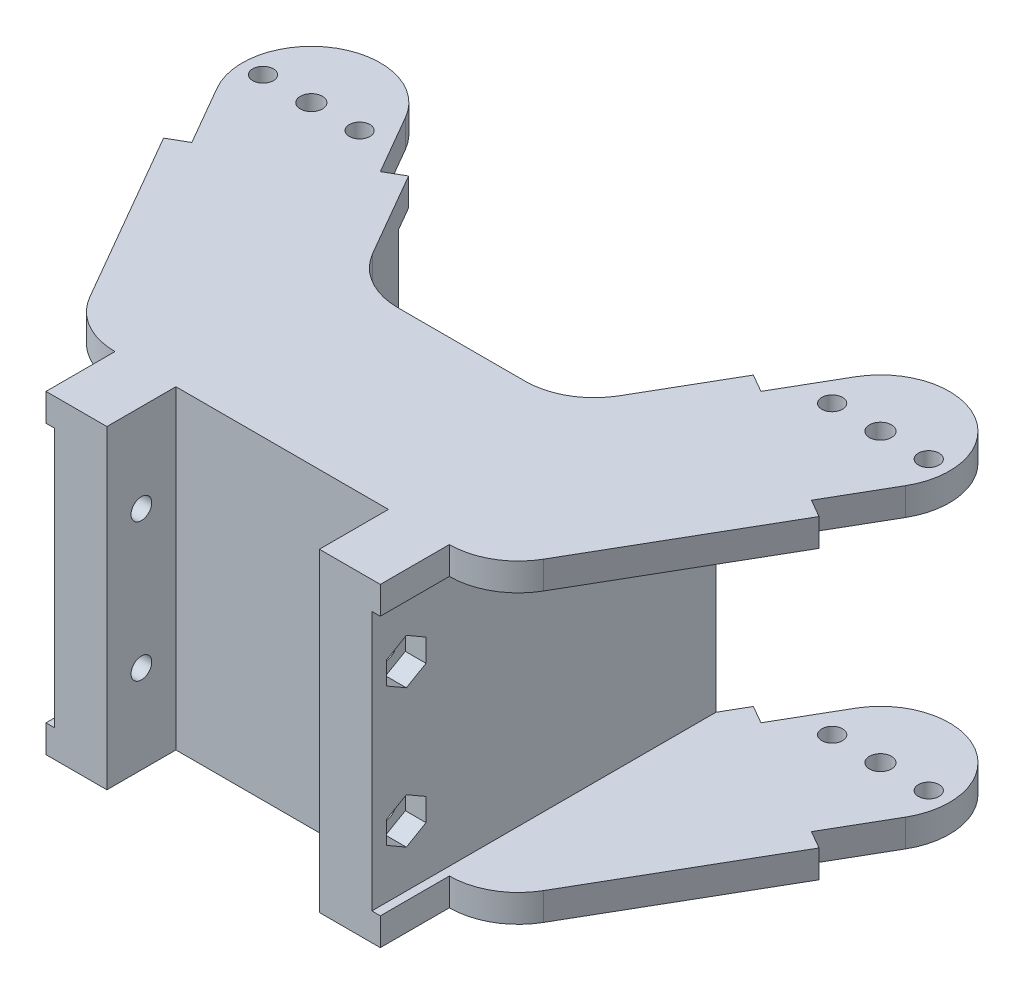
SolidWorks part; units mm, degrees
ref_plane "Alzado" through (0, 0, 0) normal (0, 0, 1) x (1, 0, 0)
ref_plane "Planta" through (0, 0, 0) normal (0, 1, 0) x (1, 0, 0)
ref_plane "Vista lateral" through (0, 0, 0) normal (1, 0, 0) x (0, 0, -1)
ref_plane "Plano1" through (0, -45.6, 0) normal (0, -1, 0) x (1, 0, 0)
sketch "Croquis1" plane through (0, -45.6, 0) normal (0, -1, 0) x (1, 0, 0)
  line L0 (65.4682, 45.4711) -> (17.0152, 45.4711)
  line L1 (8.3549, 40.4711) -> (-6.2583, 15.1603)
  line L2 (-6.2583, 15.1603) -> (-3.6603, 13.6603)
  line L3 (-3.6603, 13.6603) -> (-8.6603, 5)
  line L4 (8.6603, -5) -> (13.6603, 3.6603)
  line L5 (13.6603, 3.6603) -> (16.2583, 2.1603)
  line L6 (16.2583, 2.1603) -> (26.2528, 19.4711)
  line L7 (26.2528, 19.4711) -> (56.2306, 19.4711)
  line L8 (56.2306, 19.4711) -> (66.225, 2.1603)
  line L9 (66.225, 2.1603) -> (68.8231, 3.6603)
  line L10 (68.8231, 3.6603) -> (73.8231, -5)
  line L11 (91.1436, 5) -> (86.1436, 13.6603)
  line L12 (86.1436, 13.6603) -> (88.7417, 15.1603)
  line L13 (88.7417, 15.1603) -> (74.1284, 40.4711)
  arc A0 (74.1284, 40.4711) -> (65.4682, 45.4711) centre (65.4682, 35.4711) ccw
  arc A1 (17.0152, 45.4711) -> (8.3549, 40.4711) centre (17.0152, 35.4711) ccw
  arc A2 (-8.6603, 5) -> (8.6603, -5) centre (0, 0) ccw
  arc A3 (73.8231, -5) -> (91.1436, 5) centre (82.4833, 0) ccw
extrude "Saliente-Extruir1" add sketch "Croquis1" against normal blind 45.6
ref_plane "Plano2" through (0, -4, 0) normal (0, 1, 0) x (1, 0, 0)
sketch "Croquis2" plane through (0, -4, 0) normal (0, 1, 0) x (1, 0, 0)
  line L0 (64.2417, -45.4711) -> (65.4682, -45.4711)
  line L1 (74.1284, -40.4711) -> (88.7417, -15.1603)
  line L2 (88.7417, -15.1603) -> (86.1436, -13.6603)
  line L3 (86.1436, -13.6603) -> (91.1436, -5)
  line L4 (73.8231, 5) -> (68.8231, -3.6603)
  line L5 (68.8231, -3.6603) -> (66.225, -2.1603)
  line L6 (66.225, -2.1603) -> (64.2417, -5.5955)
  line L7 (64.2417, -5.5955) -> (64.2417, -45.4711)
  arc A0 (65.4682, -45.4711) -> (74.1284, -40.4711) centre (65.4682, -35.4711) ccw
  arc A1 (91.1436, -5) -> (73.8231, 5) centre (82.4833, 0) ccw
extrude "Cortar-Extruir1" cut sketch "Croquis2" against normal blind 37.6
ref_plane "Plano3" through (0, -41.6, 0) normal (0, -1, 0) x (1, 0, 0)
sketch "Croquis3" plane through (0, -41.6, 0) normal (0, -1, 0) x (1, 0, 0)
  line L0 (18.2417, 5.5955) -> (18.2417, 45.4711)
  line L1 (18.2417, 45.4711) -> (17.0152, 45.4711)
  line L2 (8.3549, 40.4711) -> (-6.2583, 15.1603)
  line L3 (-6.2583, 15.1603) -> (-3.6603, 13.6603)
  line L4 (-3.6603, 13.6603) -> (-8.6603, 5)
  line L5 (8.6603, -5) -> (13.6603, 3.6603)
  line L6 (13.6603, 3.6603) -> (16.2583, 2.1603)
  line L7 (16.2583, 2.1603) -> (18.2417, 5.5955)
  arc A0 (17.0152, 45.4711) -> (8.3549, 40.4711) centre (17.0152, 35.4711) ccw
  arc A1 (-8.6603, 5) -> (8.6603, -5) centre (0, 0) ccw
extrude "Cortar-Extruir2" cut sketch "Croquis3" against normal blind 37.6
sketch "Croquis4" plane through (0, 0, 45.4711) normal (0, 0, 1) x (1, 0, 0)
  line L0 (65.4682, -45.6) -> (17.0152, -45.6)
  line L1 (17.0152, -45.6) -> (17.0152, -41.6)
  line L2 (17.0152, -41.6) -> (18.2417, -41.6)
  line L3 (18.2417, -41.6) -> (18.2417, -4)
  line L4 (18.2417, -4) -> (17.0152, -4)
  line L5 (17.0152, -4) -> (17.0152, 0)
  line L6 (17.0152, 0) -> (65.4682, 0)
  line L7 (65.4682, 0) -> (65.4682, -4)
  line L8 (65.4682, -4) -> (64.2417, -4)
  line L9 (64.2417, -4) -> (64.2417, -41.6)
  line L10 (64.2417, -41.6) -> (65.4682, -41.6)
  line L11 (65.4682, -41.6) -> (65.4682, -45.6)
extrude "Saliente-Extruir2" add sketch "Croquis4" along normal blind 10
sketch "Croquis5" plane through (0, 0, 0) normal (0, 1, 0) x (-1, 0, 0)
  line L0 (-25.8417, 55.4711) -> (-56.6417, 55.4711)
  line L1 (-56.6417, 55.4711) -> (-56.6417, 45.4711)
  line L2 (-56.6417, 45.4711) -> (-25.8417, 45.4711)
  line L3 (-25.8417, 45.4711) -> (-25.8417, 55.4711)
extrude "Cortar-Extruir3" cut sketch "Croquis5" against normal through all
sketch "Croquis6" plane through (64.2417, 0, 0) normal (1, 0, 0) x (0, 0, -1)
  line L0 (-47.6207, -34.4446) -> (-47.6216, -31.1538)
  line L1 (-47.6216, -31.1538) -> (-50.4721, -29.5091)
  line L2 (-50.4721, -29.5091) -> (-53.3216, -31.1554)
  line L3 (-53.3216, -31.1554) -> (-53.3207, -34.4462)
  line L4 (-53.3207, -34.4462) -> (-50.4702, -36.0909)
  line L5 (-50.4702, -36.0909) -> (-47.6207, -34.4446)
extrude "Cortar-Extruir4" cut sketch "Croquis6" against normal blind 3
sketch "Croquis7" plane through (64.2417, 0, 0) normal (1, 0, 0) x (0, 0, -1)
  line L0 (-50.4702, -9.5091) -> (-53.3207, -11.1538)
  line L1 (-53.3207, -11.1538) -> (-53.3216, -14.4446)
  line L2 (-53.3216, -14.4446) -> (-50.4721, -16.0909)
  line L3 (-50.4721, -16.0909) -> (-47.6216, -14.4462)
  line L4 (-47.6216, -14.4462) -> (-47.6207, -11.1554)
  line L5 (-47.6207, -11.1554) -> (-50.4702, -9.5091)
extrude "Cortar-Extruir5" cut sketch "Croquis7" against normal blind 3
hole_wizard "Diámetro de taladro Ø3.0 (3)1" positions "Croquis9" profile "Croquis8" hole size "Ø3.0" standard "Ansi Metric"
sketch "Croquis9" plane through (25.8417, 0, 0) normal (1, 0, 0) x (0, 0, -1)
  point P0 (-50.4711, -12.8)
  point P1 (-50.4711, -32.8)
sketch "Croquis8" plane through (25.8417, -12.8, 50.4711) normal (0, 1, 0) x (0, 0, -1)
  line L0 (0, 0) -> (0, 35.8417)
  line L1 (0, 35.8417) -> (1.5, 35.8417)
  line L2 (1.5, 35.8417) -> (1.5, 0)
  line L5 (1.5, 0) -> (0, 0)
  line L11 (0, -6.35) -> (0, 107.95) construction
  dimension "Diámetro de taladro hasta el siguiente" = 3
  dimension "Profundidad de taladro hasta el siguiente" = 35.8417
hole_wizard "Diámetro de taladro Ø3.0 (3)2" positions "Croquis11" profile "Croquis10" hole size "Ø3.0" standard "Ansi Metric"
sketch "Croquis11" plane through (0, -45.6, 0) normal (0, -1, 0) x (-1, 0, 0)
  point P0 (-89.4833, 0)
  point P1 (-75.4833, 0)
sketch "Croquis10" plane through (89.4833, -45.6, 0) normal (1, 0, 0) x (0, 0, -1)
  line L0 (0, 0) -> (0, 4)
  line L1 (0, 4) -> (1.5, 4)
  line L2 (1.5, 4) -> (1.5, 0)
  line L5 (1.5, 0) -> (0, 0)
  line L11 (0, -6.35) -> (0, 107.95) construction
  dimension "Diámetro de taladro hasta el siguiente" = 3
  dimension "Profundidad de taladro hasta el siguiente" = 4
hole_wizard "Diámetro de taladro Ø3.2 (3.2)1" positions "Croquis13" profile "Croquis12" hole size "Ø3.2" standard "Ansi Metric"
sketch "Croquis13" plane through (0, -45.6, 0) normal (0, -1, 0) x (-1, 0, 0)
  point P0 (-82.4833, 0)
sketch "Croquis12" plane through (82.4833, -45.6, 0) normal (1, 0, 0) x (0, 0, -1)
  line L0 (0, 0) -> (0, 4)
  line L1 (0, 4) -> (1.6, 4)
  line L2 (1.6, 4) -> (1.6, 0)
  line L5 (1.6, 0) -> (0, 0)
  line L11 (0, -6.35) -> (0, 107.95) construction
  dimension "Diámetro de taladro hasta el siguiente" = 3.2
  dimension "Profundidad de taladro hasta el siguiente" = 4
hole_wizard "Diámetro de taladro Ø3.0 (3)3" positions "Croquis15" profile "Croquis14" hole size "Ø3.0" standard "Ansi Metric"
sketch "Croquis15" plane through (0, -4, 0) normal (0, -1, 0) x (-1, 0, 0)
  point P0 (-7, 0)
  point P1 (7, 0)
sketch "Croquis14" plane through (7, -4, 0) normal (1, 0, 0) x (0, 0, -1)
  line L0 (0, 0) -> (0, 4)
  line L1 (0, 4) -> (1.5, 4)
  line L2 (1.5, 4) -> (1.5, 0)
  line L5 (1.5, 0) -> (0, 0)
  line L11 (0, -6.35) -> (0, 107.95) construction
  dimension "Diámetro de taladro hasta el siguiente" = 3
  dimension "Profundidad de taladro hasta el siguiente" = 4
hole_wizard "Diámetro de taladro Ø3.0 (3)4" positions "Croquis17" profile "Croquis16" hole size "Ø3.0" standard "Ansi Metric"
sketch "Croquis17" plane through (0, -41.6, 0) normal (0, 1, 0) x (1, 0, 0)
  point P0 (7, 0)
  point P1 (-7, 0)
sketch "Croquis16" plane through (7, -41.6, 0) normal (1, 0, 0) x (0, 0, 1)
  line L0 (0, 0) -> (0, 4)
  line L1 (0, 4) -> (1.5, 4)
  line L2 (1.5, 4) -> (1.5, 0)
  line L5 (1.5, 0) -> (0, 0)
  line L11 (0, -6.35) -> (0, 107.95) construction
  dimension "Diámetro de taladro hasta el siguiente" = 3
  dimension "Profundidad de taladro hasta el siguiente" = 4
hole_wizard "Diámetro de taladro Ø3.0 (3)5" positions "Croquis19" profile "Croquis18" hole size "Ø3.0" standard "Ansi Metric"
sketch "Croquis19" plane through (0, 0, 0) normal (0, 1, 0) x (1, 0, 0)
  point P0 (89.4833, 0)
  point P1 (75.4833, 0)
sketch "Croquis18" plane through (89.4833, 0, 0) normal (1, 0, 0) x (0, 0, 1)
  line L0 (0, 0) -> (0, 45.6)
  line L1 (0, 45.6) -> (1.5, 45.6)
  line L2 (1.5, 45.6) -> (1.5, 0)
  line L5 (1.5, 0) -> (0, 0)
  line L11 (0, -6.35) -> (0, 107.95) construction
  dimension "Diámetro de taladro hasta el siguiente" = 3
  dimension "Profundidad de taladro hasta el siguiente" = 45.6
hole_wizard "Diámetro de taladro Ø3.2 (3.2)2" positions "Croquis21" profile "Croquis20" hole size "Ø3.2" standard "Ansi Metric"
sketch "Croquis21" plane through (0, -4, 0) normal (0, -1, 0) x (-1, 0, 0)
  point P0 (0, 0)
sketch "Croquis20" plane through (0, -4, 0) normal (1, 0, 0) x (0, 0, -1)
  line L0 (0, 0) -> (0, 4)
  line L1 (0, 4) -> (1.6, 4)
  line L2 (1.6, 4) -> (1.6, 0)
  line L5 (1.6, 0) -> (0, 0)
  line L11 (0, -6.35) -> (0, 107.95) construction
  dimension "Diámetro de taladro hasta el siguiente" = 3.2
  dimension "Profundidad de taladro hasta el siguiente" = 4
hole_wizard "Diámetro de taladro Ø3.2 (3.2)3" positions "Croquis23" profile "Croquis22" hole size "Ø3.2" standard "Ansi Metric"
sketch "Croquis23" plane through (0, -41.6, 0) normal (0, 1, 0) x (1, 0, 0)
  point P0 (0, 0)
sketch "Croquis22" plane through (0, -41.6, 0) normal (1, 0, 0) x (0, 0, 1)
  line L0 (0, 0) -> (0, 4)
  line L1 (0, 4) -> (1.6, 4)
  line L2 (1.6, 4) -> (1.6, 0)
  line L5 (1.6, 0) -> (0, 0)
  line L11 (0, -6.35) -> (0, 107.95) construction
  dimension "Diámetro de taladro hasta el siguiente" = 3.2
  dimension "Profundidad de taladro hasta el siguiente" = 4
hole_wizard "Diámetro de taladro Ø3.2 (3.2)4" positions "Croquis25" profile "Croquis24" hole size "Ø3.2" standard "Ansi Metric"
sketch "Croquis25" plane through (0, 0, 0) normal (0, 1, 0) x (1, 0, 0)
  point P0 (82.4833, 0)
sketch "Croquis24" plane through (82.4833, 0, 0) normal (1, 0, 0) x (0, 0, 1)
  line L0 (0, 0) -> (0, 45.6)
  line L1 (0, 45.6) -> (1.6, 45.6)
  line L2 (1.6, 45.6) -> (1.6, 0)
  line L5 (1.6, 0) -> (0, 0)
  line L11 (0, -6.35) -> (0, 107.95) construction
  dimension "Diámetro de taladro hasta el siguiente" = 3.2
  dimension "Profundidad de taladro hasta el siguiente" = 45.6
hole_wizard "Diámetro de taladro Ø3.0 (3)6" positions "Croquis27" profile "Croquis26" hole size "Ø3.0" standard "Ansi Metric"
sketch "Croquis27" plane through (61.2417, 0, 0) normal (1, 0, 0) x (0, 0, -1)
  point P0 (-50.4711, -12.8)
  point P1 (-50.4711, -32.8)
sketch "Croquis26" plane through (61.2417, -12.8, 50.4711) normal (0, 1, 0) x (0, 0, -1)
  line L0 (0, 0) -> (0, 71.2417)
  line L1 (0, 71.2417) -> (1.5, 71.2417)
  line L2 (1.5, 71.2417) -> (1.5, 0)
  line L5 (1.5, 0) -> (0, 0)
  line L11 (0, -6.35) -> (0, 107.95) construction
  dimension "Diámetro de taladro hasta el siguiente" = 3
  dimension "Profundidad de taladro hasta el siguiente" = 71.2417
fillet "Redondeo1" radius 10 2 edges at (26.2528, -22.8, 19.4711) (56.2306, -22.8, 19.4711)
